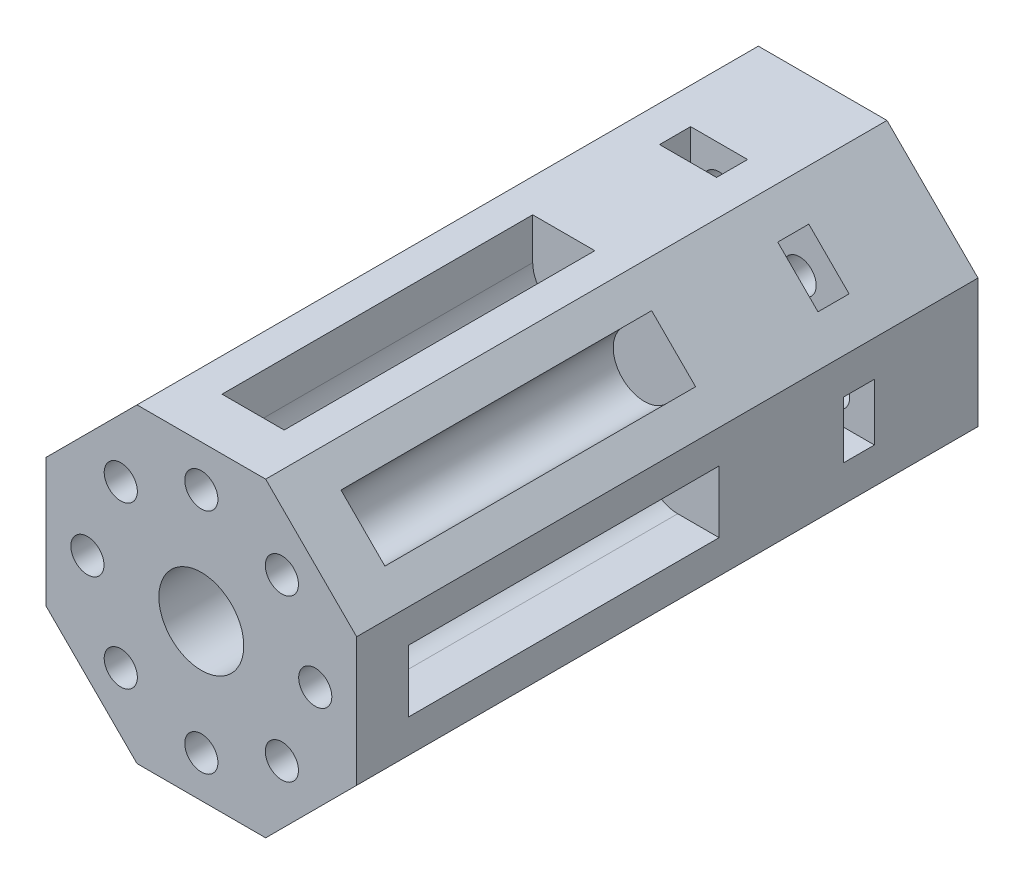
SolidWorks part; units mm, degrees
ref_plane "Alzado" through (0, 0, 0) normal (0, 0, 1) x (1, 0, 0)
ref_plane "Planta" through (0, 0, 0) normal (0, 1, 0) x (1, 0, 0)
ref_plane "Vista lateral" through (0, 0, 0) normal (1, 0, 0) x (0, 0, -1)
sketch "Croquis1" plane through (0, 0, 0) normal (0, 0, 1) x (1, 0, 0)
  line L1 (15, -6.2132) -> (15, 6.2132)
  line L2 (15, 6.2132) -> (6.2132, 15)
  line L3 (6.2132, 15) -> (-6.2132, 15)
  line L4 (-6.2132, 15) -> (-15, 6.2132)
  line L5 (-15, 6.2132) -> (-15, -6.2132)
  line L6 (-15, -6.2132) -> (-6.2132, -15)
  line L7 (-6.2132, -15) -> (6.2132, -15)
  line L8 (6.2132, -15) -> (15, -6.2132)
  circle A0 centre (0, 0) radius 15 construction
  dimension "D1" = 30
extrude "Saliente-Extruir1" add sketch "Croquis1" along normal blind 60
sketch "Croquis2" plane through (0, 0, 0) normal (0, 0, -1) x (-1, 0, 0)
  circle A0 centre (0, 11) radius 1.6
  circle A2 centre (7.7782, 7.7782) radius 1.6
  circle A3 centre (11, 0) radius 1.6
  circle A4 centre (7.7782, -7.7782) radius 1.6
  circle A5 centre (0, -11) radius 1.6
  circle A6 centre (-7.7782, -7.7782) radius 1.6
  circle A7 centre (-11, 0) radius 1.6
  circle A8 centre (-7.7782, 7.7782) radius 1.6
  point P22 (0, 0)
  dimension "D1" = 3.2
  dimension "D2" = 11
  dimension "D4" = 8
extrude "Cortar-Extruir1" cut sketch "Croquis2" against normal blind 20
sketch "Croquis3" plane through (0, 0, 0) normal (0, 0, -1) x (-1, 0, 0)
  line L0 (-2.75, 12.5877) -> (-2.75, 18.4632)
  line L1 (2.75, 12.5877) -> (0, 14.1754) construction
  line L2 (0, 14.1754) -> (-2.75, 12.5877) construction
  line L3 (-2.75, 12.5877) -> (-2.75, 9.4123)
  line L4 (-2.75, 9.4123) -> (0, 7.8246)
  line L5 (0, 7.8246) -> (2.75, 9.4123)
  line L6 (2.75, 9.4123) -> (2.75, 12.5877)
  line L7 (-15, 6.2132) -> (-6.2132, 15) construction
  line L8 (-2.75, 18.4632) -> (2.75, 23.9632)
  line L9 (2.75, 23.9632) -> (2.75, 12.5877)
  line L10 (6.9563, 10.8454) -> (11.1109, 15)
  line L11 (6.9563, 10.8454) -> (4.7109, 8.6)
  line L12 (4.7109, 8.6) -> (5.5328, 5.5328)
  line L13 (5.5328, 5.5328) -> (8.6, 4.7109)
  line L14 (8.6, 4.7109) -> (10.8454, 6.9563)
  line L15 (11.1109, 15) -> (18.8891, 15)
  line L16 (18.8891, 15) -> (10.8454, 6.9563)
  line L17 (10.8454, 6.9563) -> (10.0235, 10.0235) construction
  line L18 (10.0235, 10.0235) -> (6.9563, 10.8454) construction
  line L19 (12.5877, 2.75) -> (18.4632, 2.75)
  line L20 (12.5877, 2.75) -> (9.4123, 2.75)
  line L21 (9.4123, 2.75) -> (7.8246, 0)
  line L22 (7.8246, 0) -> (9.4123, -2.75)
  line L23 (9.4123, -2.75) -> (12.5877, -2.75)
  line L24 (18.4632, 2.75) -> (23.9632, -2.75)
  line L25 (23.9632, -2.75) -> (12.5877, -2.75)
  line L26 (12.5877, -2.75) -> (14.1754, 0) construction
  line L27 (14.1754, 0) -> (12.5877, 2.75) construction
  line L28 (10.8454, -6.9563) -> (15, -11.1109)
  line L29 (10.8454, -6.9563) -> (8.6, -4.7109)
  line L30 (8.6, -4.7109) -> (5.5328, -5.5328)
  line L31 (5.5328, -5.5328) -> (4.7109, -8.6)
  line L32 (4.7109, -8.6) -> (6.9563, -10.8454)
  line L33 (15, -11.1109) -> (15, -18.8891)
  line L34 (15, -18.8891) -> (6.9563, -10.8454)
  line L35 (6.9563, -10.8454) -> (10.0235, -10.0235) construction
  line L36 (10.0235, -10.0235) -> (10.8454, -6.9563) construction
  line L37 (2.75, -12.5877) -> (2.75, -18.4632)
  line L38 (2.75, -12.5877) -> (2.75, -9.4123)
  line L39 (2.75, -9.4123) -> (0, -7.8246)
  line L40 (0, -7.8246) -> (-2.75, -9.4123)
  line L41 (-2.75, -9.4123) -> (-2.75, -12.5877)
  line L42 (2.75, -18.4632) -> (-2.75, -23.9632)
  line L43 (-2.75, -23.9632) -> (-2.75, -12.5877)
  line L44 (-2.75, -12.5877) -> (0, -14.1754) construction
  line L45 (0, -14.1754) -> (2.75, -12.5877) construction
  line L46 (-6.9563, -10.8454) -> (-11.1109, -15)
  line L47 (-6.9563, -10.8454) -> (-4.7109, -8.6)
  line L48 (-4.7109, -8.6) -> (-5.5328, -5.5328)
  line L49 (-5.5328, -5.5328) -> (-8.6, -4.7109)
  line L50 (-8.6, -4.7109) -> (-10.8454, -6.9563)
  line L51 (-11.1109, -15) -> (-18.8891, -15)
  line L52 (-18.8891, -15) -> (-10.8454, -6.9563)
  line L53 (-10.8454, -6.9563) -> (-10.0235, -10.0235) construction
  line L54 (-10.0235, -10.0235) -> (-6.9563, -10.8454) construction
  line L55 (-12.5877, -2.75) -> (-18.4632, -2.75)
  line L56 (-12.5877, -2.75) -> (-9.4123, -2.75)
  line L57 (-9.4123, -2.75) -> (-7.8246, 0)
  line L58 (-7.8246, 0) -> (-9.4123, 2.75)
  line L59 (-9.4123, 2.75) -> (-12.5877, 2.75)
  line L60 (-18.4632, -2.75) -> (-23.9632, 2.75)
  line L61 (-23.9632, 2.75) -> (-12.5877, 2.75)
  line L62 (-12.5877, 2.75) -> (-14.1754, 0) construction
  line L63 (-14.1754, 0) -> (-12.5877, -2.75) construction
  line L64 (-10.8454, 6.9563) -> (-15, 11.1109)
  line L65 (-10.8454, 6.9563) -> (-8.6, 4.7109)
  line L66 (-8.6, 4.7109) -> (-5.5328, 5.5328)
  line L67 (-5.5328, 5.5328) -> (-4.7109, 8.6)
  line L68 (-4.7109, 8.6) -> (-6.9563, 10.8454)
  line L69 (-15, 11.1109) -> (-15, 18.8891)
  line L70 (-15, 18.8891) -> (-6.9563, 10.8454)
  line L71 (-6.9563, 10.8454) -> (-10.0235, 10.0235) construction
  line L72 (-10.0235, 10.0235) -> (-10.8454, 6.9563) construction
  circle A0 centre (0, 11) radius 2.75 construction
  circle A1 centre (7.7782, 7.7782) radius 2.75 construction
  circle A2 centre (11, 0) radius 2.75 construction
  circle A3 centre (7.7782, -7.7782) radius 2.75 construction
  circle A4 centre (0, -11) radius 2.75 construction
  circle A5 centre (-7.7782, -7.7782) radius 2.75 construction
  circle A6 centre (-11, 0) radius 2.75 construction
  circle A7 centre (-7.7782, 7.7782) radius 2.75 construction
  point P86 (0, 0)
  dimension "D1" = 5.5
  dimension "D2" = 8
extrude "Cortar-Extruir2" cut sketch "Croquis3" against normal blind 3 from offset 10 offset against normal yes
sketch "Croquis4" plane through (0, 0, 0) normal (0, 0, -1) x (-1, 0, 0)
  circle A0 centre (0, 0) radius 4.1
  dimension "D1" = 8.2
extrude "Cortar-Extruir3" cut sketch "Croquis4" against normal through all
sketch "Croquis6" plane through (0, 0, 60) normal (0, 0, 1) x (1, 0, 0)
  circle A0 centre (0, 11) radius 1.6
  circle A1 centre (7.7782, 7.7782) radius 1.6
  circle A2 centre (11, 0) radius 1.6
  circle A3 centre (7.7782, -7.7782) radius 1.6
  circle A4 centre (0, -11) radius 1.6
  circle A5 centre (-7.7782, -7.7782) radius 1.6
  circle A6 centre (-11, 0) radius 1.6
  circle A7 centre (-7.7782, 7.7782) radius 1.6
  point P19 (0, 0)
  dimension "D1" = 3.2
  dimension "D2" = 11
  dimension "D3" = 8
extrude "Cortar-Extruir4" cut sketch "Croquis6" against normal blind 10
sketch "Croquis7" plane through (0, 0, 60) normal (0, 0, 1) x (1, 0, 0)
  line L0 (-3, 11) -> (-3, 15)
  line L1 (6.2132, 15) -> (-6.2132, 15) construction
  line L2 (-3, 15) -> (3, 15)
  line L3 (3, 15) -> (3, 11)
  line L4 (5.6569, 9.8995) -> (8.4853, 12.7279)
  line L5 (8.4853, 12.7279) -> (12.7279, 8.4853)
  line L6 (12.7279, 8.4853) -> (9.8995, 5.6569)
  line L7 (11, 3) -> (15, 3)
  line L8 (15, 3) -> (15, -3)
  line L9 (15, -3) -> (11, -3)
  line L10 (9.8995, -5.6569) -> (12.7279, -8.4853)
  line L11 (12.7279, -8.4853) -> (8.4853, -12.7279)
  line L12 (8.4853, -12.7279) -> (5.6569, -9.8995)
  line L13 (3, -11) -> (3, -15)
  line L14 (3, -15) -> (-3, -15)
  line L15 (-3, -15) -> (-3, -11)
  line L16 (-5.6569, -9.8995) -> (-8.4853, -12.7279)
  line L17 (-8.4853, -12.7279) -> (-12.7279, -8.4853)
  line L18 (-12.7279, -8.4853) -> (-9.8995, -5.6569)
  line L19 (-11, -3) -> (-15, -3)
  line L20 (-15, -3) -> (-15, 3)
  line L21 (-15, 3) -> (-11, 3)
  line L22 (-9.8995, 5.6569) -> (-12.7279, 8.4853)
  line L23 (-12.7279, 8.4853) -> (-8.4853, 12.7279)
  line L24 (-8.4853, 12.7279) -> (-5.6569, 9.8995)
  arc A0 (-3, 11) -> (3, 11) centre (0, 11) ccw
  arc A1 (5.6569, 9.8995) -> (9.8995, 5.6569) centre (7.7782, 7.7782) ccw
  arc A2 (11, 3) -> (11, -3) centre (11, 0) ccw
  arc A3 (9.8995, -5.6569) -> (5.6569, -9.8995) centre (7.7782, -7.7782) ccw
  arc A4 (3, -11) -> (-3, -11) centre (0, -11) ccw
  arc A5 (-5.6569, -9.8995) -> (-9.8995, -5.6569) centre (-7.7782, -7.7782) ccw
  arc A6 (-11, -3) -> (-11, 3) centre (-11, 0) ccw
  arc A7 (-9.8995, 5.6569) -> (-5.6569, 9.8995) centre (-7.7782, 7.7782) ccw
  point P46 (0, 0)
  dimension "D1" = 3
  dimension "D2" = 8
extrude "Cortar-Extruir5" cut sketch "Croquis7" against normal blind 30 from offset 5 offset against normal yes
